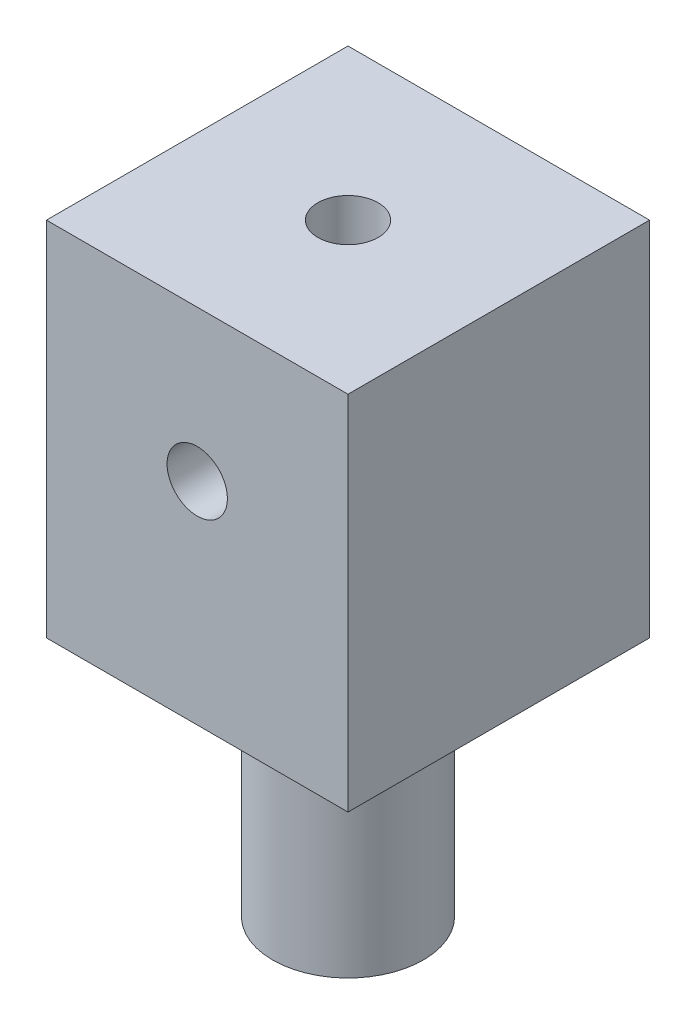
SolidWorks part; units mm, degrees
ref_plane "Front Plane" through (0, 0, 0) normal (0, 0, 1) x (1, 0, 0)
ref_plane "Top Plane" through (0, 0, 0) normal (0, 1, 0) x (1, 0, 0)
ref_plane "Right Plane" through (0, 0, 0) normal (1, 0, 0) x (0, 0, -1)
sketch "Sketch3" plane through (0, 0, 0) normal (0, 1, 0) x (1, 0, 0)
  circle A0 centre (0, 0) radius 15.875
  dimension "D1" = 31.75
extrude "Boss-Extrude1" add sketch "Sketch3" along normal blind 63.5
sketch "Sketch4" plane through (0, 63.5, 0) normal (0, 1, 0) x (1, 0, 0)
  line L1 (-31.75, -31.75) -> (31.75, -31.75)
  line L2 (-31.75, -31.75) -> (-31.75, 31.75)
  line L3 (-31.75, 31.75) -> (31.75, 31.75)
  line L4 (31.75, -31.75) -> (31.75, 31.75)
  line L5 (-31.75, -31.75) -> (31.75, 31.75) construction
  line L6 (-31.75, 31.75) -> (31.75, -31.75) construction
  circle A0 centre (0, 0) radius 6.35
  circle A1 centre (0, 0) radius 15.875
  circle A2 centre (0, 0) radius 15.875
  circle M6 centre (0, 0) radius 15.875
  dimension "D4" = 12.7
  dimension "D2" = 63.5
  dimension "D3" = 63.5
  dimension "D1" = 0
extrude "Boss-Extrude2" add sketch "Sketch4" along normal blind 76.2 from offset 12.7 separate body contours A0 M6 | L1 L4 L3 L2 M6 offset against normal yes
sketch "Sketch5" plane through (0, 0, 31.75) normal (0, 0, 1) x (1, 0, 0)
  line L1 (-31.75, 127) -> (31.75, 127)
  line L2 (-31.75, 127) -> (-31.75, 63.5)
  line L3 (-31.75, 63.5) -> (31.75, 63.5)
  line L4 (-31.75, 50.8) -> (31.75, 50.8)
  line L5 (31.75, 50.8) -> (31.75, 127)
  line L6 (-31.75, 50.8) -> (31.75, 50.8)
  line L7 (-31.75, 127) -> (-31.75, 50.8)
  line L9 (31.75, 50.8) -> (31.75, 127)
  line L11 (-31.75, 127) -> (-31.75, 50.8)
  line L12 (31.75, 127) -> (31.75, 63.5)
  line L13 (-31.75, 127) -> (31.75, 63.5) construction
  line L14 (-31.75, 63.5) -> (31.75, 127) construction
  line L18 (31.75, 127) -> (-31.75, 127)
  line L19 (31.75, 127) -> (-31.75, 127)
  circle A0 centre (0, 95.25) radius 6.35
  point P7 (0, 95.25)
  dimension "D3" = 12.7
  dimension "D2" = 63.5
  dimension "D1" = 0
extrude "Cut-Extrude1" cut sketch "Sketch5" against normal up to next contours A0
combine bodies "Combine1" operation type add bodies to combine 101 103
